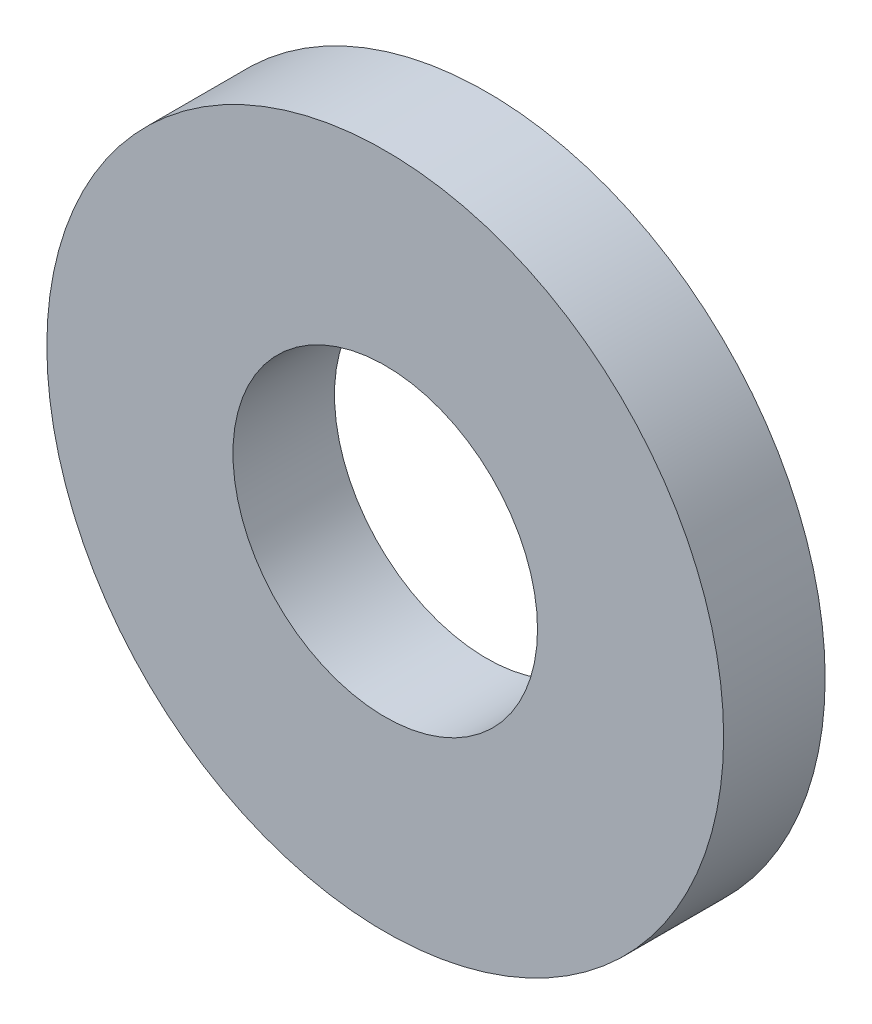
SolidWorks part; units mm, degrees
material "Galvanized Steel"
ref_plane "Front Plane" through (0, 0, 0) normal (0, 0, 1) x (1, 0, 0)
ref_plane "Top Plane" through (0, 0, 0) normal (0, 1, 0) x (1, 0, 0)
ref_plane "Right Plane" through (0, 0, 0) normal (1, 0, 0) x (0, 0, -1)
sketch "Sketch1" plane through (0, 0, 0) normal (0, 0, 1) x (1, 0, 0)
  circle A0 centre (0, 0) radius 4.5
  circle A1 centre (0, 0) radius 10
  dimension "D1" = 9
  dimension "D2" = 20
extrude "Boss-Extrude1" add sketch "Sketch1" along normal blind 3
